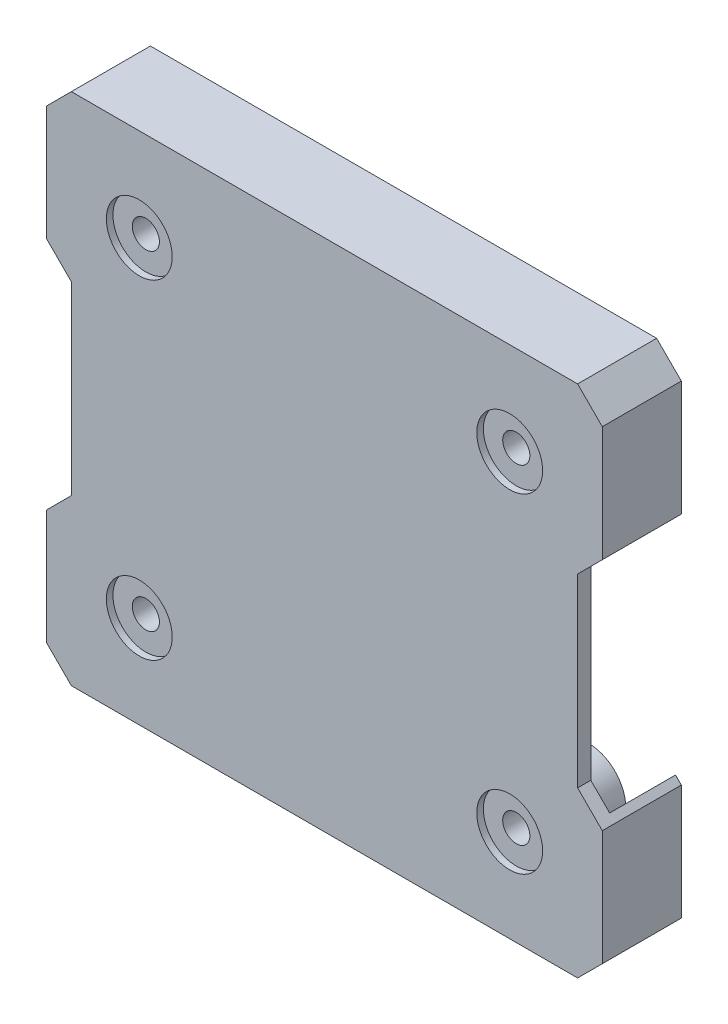
SolidWorks part; units mm, degrees
ref_plane "前视基准面" through (0, 0, 0) normal (0, 0, 1) x (1, 0, 0)
ref_plane "上视基准面" through (0, 0, 0) normal (0, 1, 0) x (1, 0, 0)
ref_plane "右视基准面" through (0, 0, 0) normal (1, 0, 0) x (0, 0, -1)
sketch "草图1" plane through (0, 0, 0) normal (0, 0, 1) x (1, 0, 0)
  line L1 (-33.75, 31.25) -> (33.75, 31.25)
  line L2 (-33.75, 31.25) -> (-33.75, -31.25)
  line L3 (-33.75, -31.25) -> (33.75, -31.25)
  line L4 (33.75, 31.25) -> (33.75, -31.25)
  line L5 (-33.75, 31.25) -> (33.75, -31.25) construction
  line L6 (-33.75, -31.25) -> (33.75, 31.25) construction
  point P0 (0, 0)
  dimension "D1" = 62.5
  dimension "D2" = 67.5
extrude "凸台-拉伸1" add sketch "草图1" along normal blind 1.6
sketch "草图2" plane through (0, 0, 1.6) normal (0, 0, 1) x (1, 0, 0)
  line L0 (-30.75, 11.25) -> (-30.75, -11.25)
  line L1 (30.75, 11.25) -> (30.75, -11.25)
  line L2 (-33.75, 31.25) -> (-33.75, -31.25) construction
  line L3 (33.75, -31.25) -> (33.75, 31.25) construction
  line L4 (-30.75, 11.25) -> (-33.75, 14.25)
  line L5 (-33.75, 14.25) -> (-33.75, -14.25)
  line L6 (-33.75, -14.25) -> (-30.75, -11.25)
  line L7 (30.75, 11.25) -> (33.75, 14.25)
  line L8 (33.75, 14.25) -> (33.75, -14.25)
  line L9 (33.75, -14.25) -> (30.75, -11.25)
  line L11 (-22.5, -20) -> (22.5, -20) construction
  line L12 (-22.5, -20) -> (-22.5, 20) construction
  line L13 (-22.5, 20) -> (22.5, 20) construction
  line L14 (22.5, -20) -> (22.5, 20) construction
  line L15 (-22.5, -20) -> (22.5, 20) construction
  line L16 (-22.5, 20) -> (22.5, -20) construction
  circle A0 centre (-22.5, 20) radius 1.65
  circle A1 centre (22.5, 20) radius 1.65
  circle A2 centre (22.5, -20) radius 1.65
  circle A3 centre (-22.5, -20) radius 1.65
  point P4 (-30.75, 0)
  point P5 (30.75, 0)
  point P11 (0, 0)
  dimension "D8" = 3.3
  dimension "D1" = 22.5
  dimension "D2" = 3
  dimension "D3" = 3
  dimension "D4" = 135
  dimension "D5" = 135
  dimension "D6" = 135
  dimension "D7" = 135
  dimension "D9" = 40
  dimension "D10" = 45
extrude "切除-拉伸1" cut sketch "草图2" against normal blind 10
chamfer "倒角1" distance 3 angle 45 4 edges at (-33.75, -31.25, 0.8) (33.75, -31.25, 0.8) (33.75, 31.25, 0.8) (-33.75, 31.25, 0.8)
sketch "草图3" plane through (0, 0, 0) normal (0, 0, -1) x (-1, 0, 0)
  line L1 (-19.9019, 20) -> (-21.201, 22.25)
  line L2 (-21.201, 22.25) -> (-23.799, 22.25)
  line L3 (-23.799, 22.25) -> (-25.0981, 20)
  line L4 (-25.0981, 20) -> (-23.799, 17.75)
  line L5 (-23.799, 17.75) -> (-21.201, 17.75)
  line L6 (-21.201, 17.75) -> (-19.9019, 20)
  line L7 (25.0981, 20) -> (23.799, 22.25)
  line L8 (23.799, 22.25) -> (21.201, 22.25)
  line L9 (21.201, 22.25) -> (19.9019, 20)
  line L10 (19.9019, 20) -> (21.201, 17.75)
  line L11 (21.201, 17.75) -> (23.799, 17.75)
  line L12 (23.799, 17.75) -> (25.0981, 20)
  line L13 (25.0981, -20) -> (23.799, -17.75)
  line L14 (23.799, -17.75) -> (21.201, -17.75)
  line L15 (21.201, -17.75) -> (19.9019, -20)
  line L16 (19.9019, -20) -> (21.201, -22.25)
  line L17 (21.201, -22.25) -> (23.799, -22.25)
  line L18 (23.799, -22.25) -> (25.0981, -20)
  line L19 (-19.9019, -20) -> (-21.201, -17.75)
  line L20 (-21.201, -17.75) -> (-23.799, -17.75)
  line L21 (-23.799, -17.75) -> (-25.0981, -20)
  line L22 (-25.0981, -20) -> (-23.799, -22.25)
  line L23 (-23.799, -22.25) -> (-21.201, -22.25)
  line L24 (-21.201, -22.25) -> (-19.9019, -20)
  circle A0 centre (-22.5, 20) radius 1.65
  circle A2 centre (22.5, 20) radius 1.65
  circle A4 centre (22.5, -20) radius 1.65
  circle A6 centre (-22.5, -20) radius 1.65
  circle A8 centre (-22.5, 20) radius 2.25 construction
  circle A9 centre (22.5, 20) radius 2.25 construction
  circle A10 centre (22.5, -20) radius 2.25 construction
  circle A11 centre (-22.5, -20) radius 2.25 construction
  dimension "D1" = 3.3
  dimension "D2" = 4.5
extrude "凸台-拉伸2" add sketch "草图3" along normal blind 4
sketch "草图4" plane through (0, 0, 1.6) normal (0, 0, 1) x (1, 0, 0)
  circle A0 centre (-22.5, 20) radius 4
  circle A1 centre (22.5, 20) radius 4
  circle A2 centre (22.5, -20) radius 4
  circle A3 centre (-22.5, -20) radius 4
  dimension "D1" = 8
extrude "切除-拉伸2" cut sketch "草图4" against normal blind 0.8
sketch "草图5" plane through (0, 0, 0) normal (0, 0, -1) x (-1, 0, 0)
  line L0 (-21.201, -22.25) -> (-19.9019, -20) construction
  line L1 (-19.9019, -20) -> (-21.201, -17.75) construction
  line L2 (-21.201, -17.75) -> (-23.799, -17.75) construction
  line L3 (-23.799, -17.75) -> (-25.0981, -20) construction
  line L4 (-25.0981, -20) -> (-23.799, -22.25) construction
  line L5 (-23.799, -22.25) -> (-21.201, -22.25) construction
  line L6 (23.799, -22.25) -> (25.0981, -20) construction
  line L7 (25.0981, -20) -> (23.799, -17.75) construction
  line L8 (23.799, -17.75) -> (21.201, -17.75) construction
  line L9 (21.201, -17.75) -> (19.9019, -20) construction
  line L10 (19.9019, -20) -> (21.201, -22.25) construction
  line L11 (21.201, -22.25) -> (23.799, -22.25) construction
  line L12 (23.799, 17.75) -> (25.0981, 20) construction
  line L13 (25.0981, 20) -> (23.799, 22.25) construction
  line L14 (23.799, 22.25) -> (21.201, 22.25) construction
  line L15 (21.201, 22.25) -> (19.9019, 20) construction
  line L16 (19.9019, 20) -> (21.201, 17.75) construction
  line L17 (21.201, 17.75) -> (23.799, 17.75) construction
  line L18 (-21.201, 17.75) -> (-19.9019, 20) construction
  line L19 (-19.9019, 20) -> (-21.201, 22.25) construction
  line L20 (-21.201, 22.25) -> (-23.799, 22.25) construction
  line L21 (-23.799, 22.25) -> (-25.0981, 20) construction
  line L22 (-25.0981, 20) -> (-23.799, 17.75) construction
  line L23 (-23.799, 17.75) -> (-21.201, 17.75) construction
  line L24 (-21.201, -22.25) -> (-19.9019, -20)
  line L25 (-19.9019, -20) -> (-21.201, -17.75)
  line L26 (-21.201, -17.75) -> (-23.799, -17.75)
  line L27 (-23.799, -17.75) -> (-25.0981, -20)
  line L28 (-25.0981, -20) -> (-23.799, -22.25)
  line L29 (-23.799, -22.25) -> (-21.201, -22.25)
  line L30 (23.799, -22.25) -> (25.0981, -20)
  line L31 (25.0981, -20) -> (23.799, -17.75)
  line L32 (23.799, -17.75) -> (21.201, -17.75)
  line L33 (21.201, -17.75) -> (19.9019, -20)
  line L34 (19.9019, -20) -> (21.201, -22.25)
  line L35 (21.201, -22.25) -> (23.799, -22.25)
  line L36 (23.799, 17.75) -> (25.0981, 20)
  line L37 (25.0981, 20) -> (23.799, 22.25)
  line L38 (23.799, 22.25) -> (21.201, 22.25)
  line L39 (21.201, 22.25) -> (19.9019, 20)
  line L40 (19.9019, 20) -> (21.201, 17.75)
  line L41 (21.201, 17.75) -> (23.799, 17.75)
  line L42 (-21.201, 17.75) -> (-19.9019, 20)
  line L43 (-19.9019, 20) -> (-21.201, 22.25)
  line L44 (-21.201, 22.25) -> (-23.799, 22.25)
  line L45 (-23.799, 22.25) -> (-25.0981, 20)
  line L46 (-25.0981, 20) -> (-23.799, 17.75)
  line L47 (-23.799, 17.75) -> (-21.201, 17.75)
  circle A2 centre (-22.5, 20) radius 4.5
  circle A3 centre (22.5, 20) radius 4.5
  circle A4 centre (22.5, -20) radius 4.5
  circle A5 centre (-22.5, -20) radius 4.5
  dimension "D1" = 9
extrude "凸台-拉伸3" add sketch "草图5" along normal blind 6
sketch "草图6" plane through (0, 0, 0) normal (0, 0, -1) x (-1, 0, 0)
  line L0 (-30.3358, -30.25) -> (30.3358, -30.25)
  line L1 (30.3358, -30.25) -> (32.75, -27.8358)
  line L2 (32.75, -27.8358) -> (32.75, -14.6642)
  line L3 (32.75, -14.6642) -> (29.75, -11.6642)
  line L4 (29.75, -11.6642) -> (29.75, 11.6642)
  line L5 (29.75, 11.6642) -> (32.75, 14.6642)
  line L6 (32.75, 14.6642) -> (32.75, 27.8358)
  line L7 (32.75, 27.8358) -> (30.3358, 30.25)
  line L8 (30.3358, 30.25) -> (-30.3358, 30.25)
  line L9 (-30.3358, 30.25) -> (-32.75, 27.8358)
  line L10 (-32.75, 27.8358) -> (-32.75, 14.6642)
  line L11 (-32.75, 14.6642) -> (-29.75, 11.6642)
  line L12 (-29.75, 11.6642) -> (-29.75, -11.6642)
  line L13 (-29.75, -11.6642) -> (-32.75, -14.6642)
  line L14 (-32.75, -14.6642) -> (-32.75, -27.8358)
  line L15 (-32.75, -27.8358) -> (-30.3358, -30.25)
  line L16 (-30.75, -31.25) -> (30.75, -31.25)
  line L17 (30.75, -31.25) -> (33.75, -28.25)
  line L18 (33.75, -28.25) -> (33.75, -14.25)
  line L19 (33.75, -14.25) -> (30.75, -11.25)
  line L20 (30.75, -11.25) -> (30.75, 11.25)
  line L21 (30.75, 11.25) -> (33.75, 14.25)
  line L22 (33.75, 14.25) -> (33.75, 28.25)
  line L23 (33.75, 28.25) -> (30.75, 31.25)
  line L24 (30.75, 31.25) -> (-30.75, 31.25)
  line L25 (-30.75, 31.25) -> (-33.75, 28.25)
  line L26 (-33.75, 28.25) -> (-33.75, 14.25)
  line L27 (-33.75, 14.25) -> (-30.75, 11.25)
  line L28 (-30.75, 11.25) -> (-30.75, -11.25)
  line L29 (-30.75, -11.25) -> (-33.75, -14.25)
  line L30 (-33.75, -14.25) -> (-33.75, -28.25)
  line L31 (-33.75, -28.25) -> (-30.75, -31.25)
  line L32 (-30.75, -31.25) -> (30.75, -31.25)
  line L33 (30.75, -31.25) -> (33.75, -28.25)
  line L34 (33.75, -28.25) -> (33.75, -14.25)
  line L35 (33.75, -14.25) -> (30.75, -11.25)
  line L36 (30.75, -11.25) -> (30.75, 11.25)
  line L37 (30.75, 11.25) -> (33.75, 14.25)
  line L38 (33.75, 14.25) -> (33.75, 28.25)
  line L39 (33.75, 28.25) -> (30.75, 31.25)
  line L40 (30.75, 31.25) -> (-30.75, 31.25)
  line L41 (-30.75, 31.25) -> (-33.75, 28.25)
  line L42 (-33.75, 28.25) -> (-33.75, 14.25)
  line L43 (-33.75, 14.25) -> (-30.75, 11.25)
  line L44 (-30.75, 11.25) -> (-30.75, -11.25)
  line L45 (-30.75, -11.25) -> (-33.75, -14.25)
  line L46 (-33.75, -14.25) -> (-33.75, -28.25)
  line L47 (-33.75, -28.25) -> (-30.75, -31.25)
  dimension "D1" = 0
  dimension "D2" = 1
extrude "凸台-拉伸4" add sketch "草图6" along normal blind 8
sketch "草图7" plane through (0, 0, -8) normal (0, 0, -1) x (-1, 0, 0)
  line L0 (-30.3358, -30.25) -> (30.3358, -30.25) construction
  line L1 (-5, -30.25) -> (5, -30.25)
  line L2 (-5, -30.25) -> (-5, -31.25)
  line L3 (-5, -31.25) -> (5, -31.25)
  line L4 (5, -30.25) -> (5, -31.25)
  line L5 (-30.75, -31.25) -> (30.75, -31.25) construction
  point P8 (0, -30.25)
  dimension "D1" = 10
extrude "切除-拉伸3" cut sketch "草图7" against normal blind 5
sketch "草图8" plane through (0, 0, 0) normal (0, 0, -1) x (-1, 0, 0)
  line L2 (-1.5, -11.1496) -> (-1.5, -12.1578)
  line L4 (1.5, -11.1496) -> (1.5, -12.1578)
  arc A0 (1.5, -11.1496) -> (-1.5, -11.1496) centre (0, 0) ccw
  arc A1 (1.5, -12.1578) -> (-1.5, -12.1578) centre (0, 0) ccw
  dimension "D1" = 1
  dimension "D2" = 22.5
  dimension "D3" = 1.5
  dimension "D4" = 1.5
extrude "凸台-拉伸5" add sketch "草图8" along normal blind 2
sketch "草图9" plane through (0, 0, -8) normal (0, 0, -1) x (-1, 0, 0)
  line L0 (29.75, 11.6642) -> (32.3358, 14.25)
  line L1 (-33.0429, 13.5429) -> (-32.3358, 14.25)
  line L2 (-33.75, 14.25) -> (-30.75, 11.25) construction
  line L3 (-32.75, 14.6642) -> (-29.75, 11.6642) construction
  line L4 (-33.0429, 13.5429) -> (-30.75, 11.25)
  line L5 (-30.75, 11.25) -> (-30.75, -11.25)
  line L6 (29.75, -11.6642) -> (29.75, 11.6642)
  line L7 (-32.3358, -14.25) -> (-33.0429, -13.5429)
  line L8 (-29.75, -11.6642) -> (-32.75, -14.6642) construction
  line L9 (-30.75, -11.25) -> (-33.75, -14.25) construction
  line L10 (-33.0429, -13.5429) -> (-30.75, -11.25)
  line L11 (-32.3358, -14.25) -> (-29.75, -11.6642)
  line L12 (-29.75, -11.6642) -> (-29.75, 11.6642)
  line L13 (-29.75, 11.6642) -> (-32.3358, 14.25)
  line L14 (0, 0) -> (0, -50000) construction
  line L15 (32.3358, -14.25) -> (29.75, -11.6642)
  line L16 (33.0429, -13.5429) -> (30.75, -11.25)
  line L25 (32.3358, -14.25) -> (33.0429, -13.5429)
  line L26 (30.75, 11.25) -> (30.75, -11.25)
  line L27 (33.0429, 13.5429) -> (30.75, 11.25)
  line L28 (33.0429, 13.5429) -> (32.3358, 14.25)
  dimension "D1" = 1
  dimension "D2" = 1
extrude "切除-拉伸4" cut sketch "草图9" against normal blind 8
fillet "圆角2" radius 2 2 edges at (-5, -30.75, -3) (5, -30.75, -3)
sketch "草图12" plane through (0, 0, -6) normal (0, 0, -1) x (-1, 0, 0)
  circle A0 centre (-22.5, 20) radius 1.65 construction
  circle A1 centre (-22.5, 20) radius 4.5
  circle A2 centre (-22.5, 20) radius 4.5
  circle A3 centre (22.5, 20) radius 4.5
  circle A4 centre (22.5, 20) radius 4.5
  circle A5 centre (-22.5, -20) radius 4.5
  circle A6 centre (-22.5, -20) radius 4.5
  circle A7 centre (22.5, -20) radius 4.5
  circle A8 centre (22.5, -20) radius 4.5
  circle A9 centre (-22.5, 20) radius 1.65
  circle A10 centre (22.5, 20) radius 1.65 construction
  circle A11 centre (22.5, 20) radius 1.65
  circle A12 centre (22.5, -20) radius 1.65 construction
  circle A13 centre (22.5, -20) radius 1.65
  circle A14 centre (-22.5, -20) radius 1.65 construction
  circle A15 centre (-22.5, -20) radius 1.65
  dimension "D1" = 0
  dimension "D2" = 0
  dimension "D3" = 0
  dimension "D4" = 0
extrude "凸台-拉伸7" add sketch "草图12" along normal blind 2 and the other way blind 2
